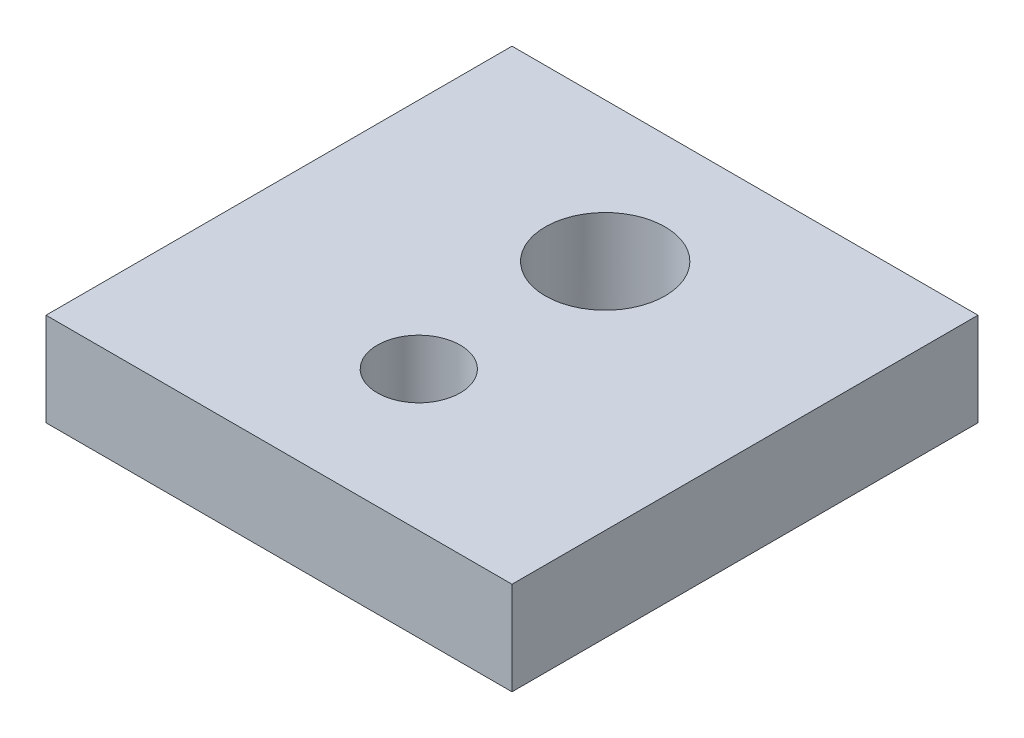
SolidWorks part; units mm, degrees
ref_plane "Front" through (0, 0, 0) normal (0, 0, 1) x (1, 0, 0)
ref_plane "Top" through (0, 0, 0) normal (0, 1, 0) x (1, 0, 0)
ref_plane "Right" through (0, 0, 0) normal (1, 0, 0) x (0, 0, -1)
sketch "Sketch1" plane through (0, 0, 0) normal (0, 1, 0) x (1, 0, 0)
  line L1 (-6.35, -6.35) -> (6.35, -6.35)
  line L2 (-6.35, -6.35) -> (-6.35, 6.35)
  line L3 (-6.35, 6.35) -> (6.35, 6.35)
  line L4 (6.35, -6.35) -> (6.35, 6.35)
  line L5 (-6.35, -6.35) -> (6.35, 6.35) construction
  line L6 (-6.35, 6.35) -> (6.35, -6.35) construction
  point P0 (0, 0)
  dimension "D1" = 12.7
  dimension "D2" = 12.7
extrude "Boss-Extrude1" add sketch "Sketch1" along normal blind 2.54
sketch "Sketch2" plane through (0, 2.54, 0) normal (0, 1, 0) x (1, 0, 0)
  line L0 (0, 6.35) -> (0, -6.35) construction
  line L1 (6.35, 6.35) -> (-6.35, 6.35) construction
  line L2 (-6.35, -6.35) -> (6.35, -6.35) construction
  point P6 (0, 2.54)
  point P7 (0, -2.54)
  point P8 (0, 4.0855)
  dimension "D1" = 3.81
  dimension "D2" = 3.81
hole_wizard "#4 Clearance Hole1" positions "3DSketch1" profile "Sketch3" hole size "#4" standard "ANSI Inch"
sketch3d "3DSketch1"
  point P0 (0, 2.54, -2.54)
sketch "Sketch3" plane through (0, 2.54, -2.54) normal (1, 0, 0) x (0, 0, 1)
  line L0 (0, 0) -> (0, 3.5196)
  line L1 (0, 3.5196) -> (1.6319, 2.539)
  line L2 (1.6319, 2.539) -> (1.6319, 0)
  line L5 (1.6319, 0) -> (0, 0)
  line L10 (0, 3.5196) -> (-1.632, 2.539) construction
  line L11 (0, -6.35) -> (0, 107.95) construction
  dimension "Hole Dia." = 3.2639
  dimension "Hole Depth" = 2.539
  dimension "Drill Angle" = 118
hole_wizard "Tap Drill for #4-40 Tap1" positions "3DSketch2" profile "Sketch4" hole size "#4-40" standard "ANSI Inch"
sketch3d "3DSketch2"
  point P0 (0, 2.54, 2.54)
sketch "Sketch4" plane through (0, 2.54, 2.54) normal (1, 0, 0) x (0, 0, 1)
  line L0 (0, 0) -> (0, 3.2182)
  line L1 (0, 3.2182) -> (1.1303, 2.539)
  line L2 (1.1303, 2.539) -> (1.1303, 0)
  line L5 (1.1303, 0) -> (0, 0)
  line L10 (0, 3.2182) -> (-1.1303, 2.539) construction
  line L11 (0, -6.35) -> (0, 107.95) construction
  dimension "Hole Dia." = 2.2606
  dimension "Hole Depth" = 2.539
  dimension "Drill Angle" = 118
